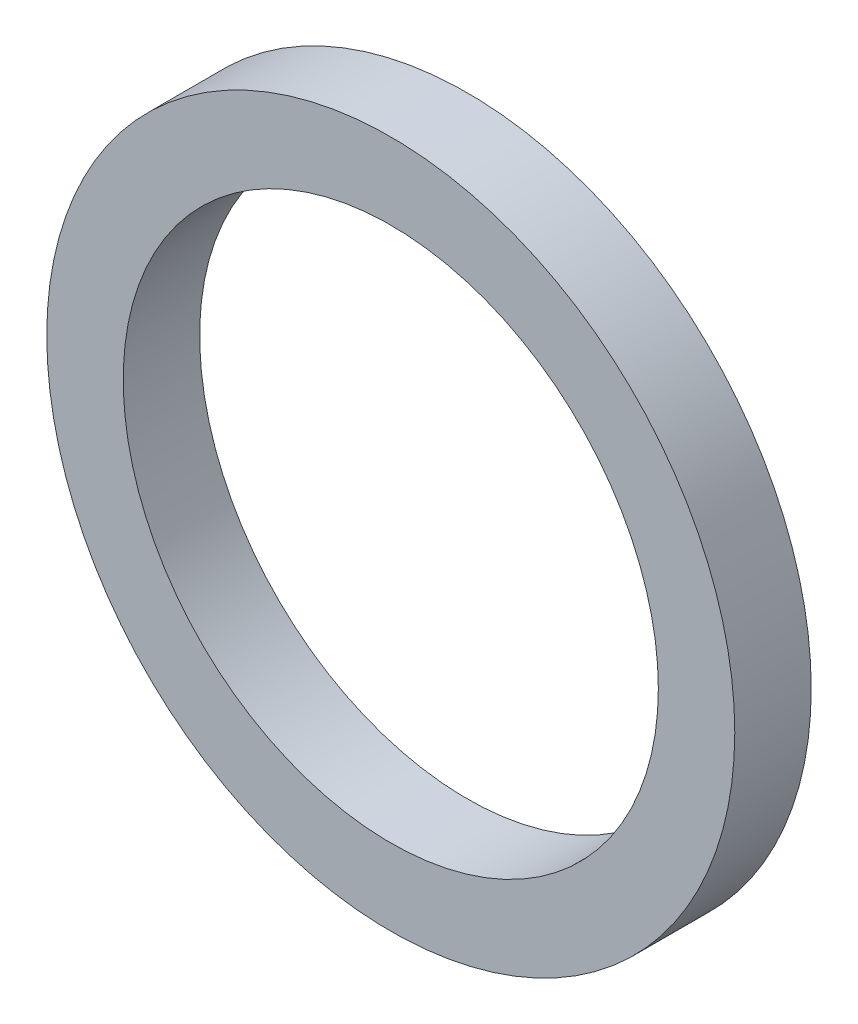
SolidWorks part; units mm, degrees
ref_plane "前视基准面" through (0, 0, 0) normal (0, 0, 1) x (1, 0, 0)
ref_plane "上视基准面" through (0, 0, 0) normal (0, 1, 0) x (1, 0, 0)
ref_plane "右视基准面" through (0, 0, 0) normal (1, 0, 0) x (0, 0, -1)
other "Configuration Table"
sketch "草图1" plane through (0, 0, 0) normal (0, 0, 1) x (1, 0, 0)
  circle A0 centre (0, 0) radius 35
  circle A1 centre (0, 0) radius 45
  dimension "D1" = 90
  dimension "D2" = 70
extrude "凸台-拉伸1" add sketch "草图1" along normal blind 10
